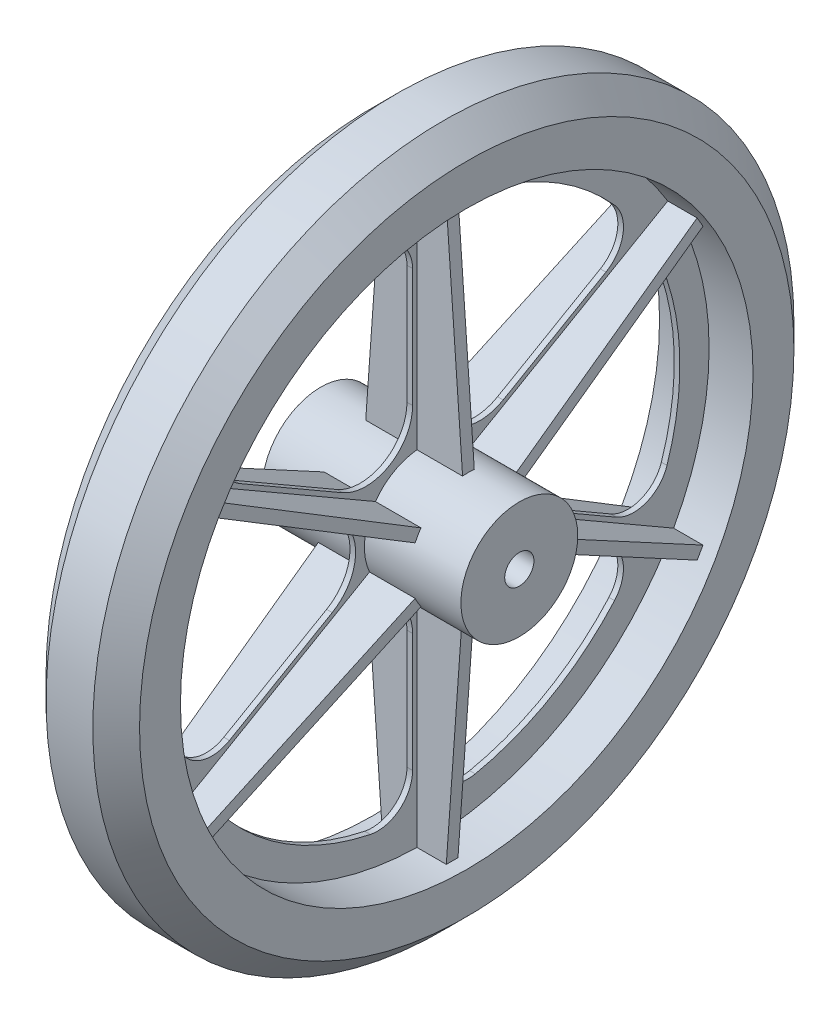
SolidWorks part; units mm, degrees
ref_plane "Front Plane" through (0, 0, 0) normal (0, 0, 1) x (1, 0, 0)
ref_plane "Top Plane" through (0, 0, 0) normal (0, 1, 0) x (1, 0, 0)
ref_plane "Right Plane" through (0, 0, 0) normal (1, 0, 0) x (0, 0, -1)
sketch "Sketch1" plane through (0, 0, 0) normal (1, 0, 0) x (0, 0, -1)
  circle A0 centre (0, 0) radius 15.875
  dimension "D2" = 31.75
extrude "Boss-Extrude1" add sketch "Sketch1" along normal blind 26.9875 and the other way blind 26.9875
sketch "Sketch2" plane through (0, 0, 0) normal (1, 0, 0) x (0, 0, -1)
  circle A0 centre (0, 0) radius 95.25
  dimension "D1" = 190.5
extrude "Boss-Extrude2" add sketch "Sketch2" along normal blind 0.762 and the other way blind 0.762
sketch "Sketch3" plane through (0, 0, 0) normal (1, 0, 0) x (0, 0, -1)
  circle A0 centre (0, 0) radius 95.25 construction
  circle A1 centre (0, 0) radius 95.25
  circle A2 centre (0, 0) radius 77.7875
  dimension "D1" = 17.4625
extrude "Boss-Extrude3" add sketch "Sketch3" along normal blind 12.7 and the other way blind 12.7
sketch "Sketch4" plane through (0, 0, 0) normal (1, 0, 0) x (0, 0, -1)
  line L0 (0, 95.25) -> (0, -95.25) construction
  line L2 (-82.4889, -47.625) -> (82.4889, 47.625) construction
  line L4 (49.7559, 31.9345) -> (21.8281, 15.8104)
  line L5 (2.7781, 59.0571) -> (2.7781, 26.8089)
  circle A0 centre (0, 0) radius 95.25 construction
  circle A1 centre (0, 0) radius 95.25 construction
  arc A2 (14.2457, 68.3819) -> (52.0976, 46.5281) centre (0, 0) cw
  arc A3 (21.8281, 15.8104) -> (2.7781, 26.8089) centre (15.4781, 26.8089) cw
  arc A4 (52.0976, 46.5281) -> (49.7559, 31.9345) centre (44.9934, 40.1834) cw
  arc A5 (14.2457, 68.3819) -> (2.7781, 59.0571) centre (12.3031, 59.0571) ccw
  dimension "D4" = 25.4
  dimension "D5" = 12.7
  dimension "D6" = 9.525
  dimension "D1" = 60
  dimension "D2" = 5.5562
  dimension "D3" = 5.5562
extrude "Cut-Extrude1" cut sketch "Sketch4" against normal through all and the other way through all
sketch "Sketch5" plane through (0, 0, 0) normal (0, 1, 0) x (1, 0, 0)
  line L1 (-14.2875, -1.5875) -> (14.2875, -1.5875)
  line L2 (-14.2875, -1.5875) -> (-14.2875, 1.5875)
  line L3 (-14.2875, 1.5875) -> (14.2875, 1.5875)
  line L4 (14.2875, -1.5875) -> (14.2875, 1.5875)
  line L5 (-14.2875, -1.5875) -> (14.2875, 1.5875) construction
  line L6 (-14.2875, 1.5875) -> (14.2875, -1.5875) construction
  line L7 (26.9875, -15.875) -> (26.9875, 15.875) construction
  point P0 (0, 0)
  dimension "D1" = 12.7
  dimension "D2" = 3.175
ref_plane "Plane1" through (0, 88.9, 0) normal (0, 1, 0) x (-1, 0, 0)
sketch "Sketch6" plane through (0, 88.9, 0) normal (0, 1, 0) x (-1, 0, 0)
  line L1 (7.9375, 1.5875) -> (-7.9375, 1.5875)
  line L2 (7.9375, 1.5875) -> (7.9375, -1.5875)
  line L3 (7.9375, -1.5875) -> (-7.9375, -1.5875)
  line L4 (-7.9375, 1.5875) -> (-7.9375, -1.5875)
  line L5 (7.9375, 1.5875) -> (-7.9375, -1.5875) construction
  line L6 (7.9375, -1.5875) -> (-7.9375, 1.5875) construction
  point P0 (0, 0)
  dimension "D1" = 15.875
  dimension "D2" = 3.175
loft "Loft1" add profiles "Sketch5", "Sketch6"
pattern_circular "CirPattern1" count 6 over 360 about axis through (0, 0, 0) along (1, 0, 0) of "Cut-Extrude1", "Loft1"
sketch "Sketch9" plane through (0, 0, 0) normal (1, 0, 0) x (0, 0, -1)
  circle A0 centre (0, 0) radius 3.9688
  dimension "D1" = 7.9375
extrude "Cut-Extrude2" cut sketch "Sketch9" against normal through all and the other way through all
chamfer "Chamfer1" distance 6.35 angle 45 2 edges at (-12.7, 0, -95.25) (12.7, 0, -95.25)
